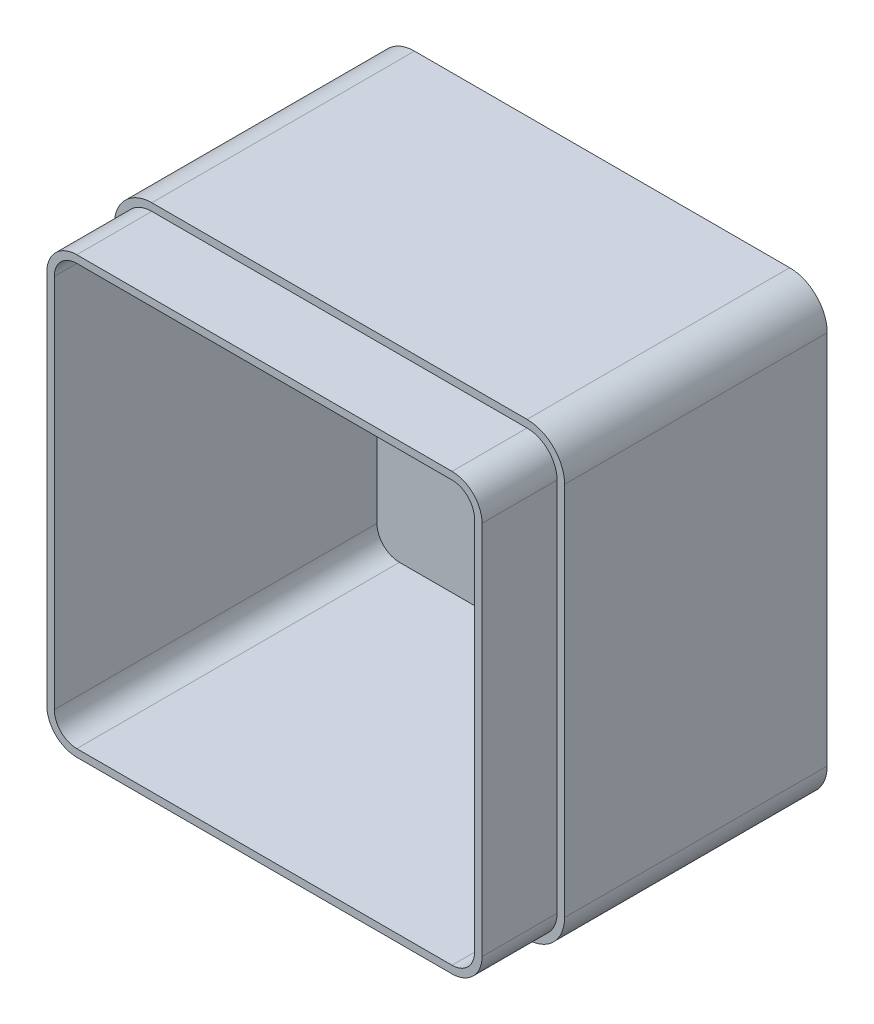
SolidWorks part; units mm, degrees
ref_plane "Front" through (0, 0, 0) normal (0, 0, 1) x (1, 0, 0)
ref_plane "Top" through (0, 0, 0) normal (0, 1, 0) x (1, 0, 0)
ref_plane "Right" through (0, 0, 0) normal (1, 0, 0) x (0, 0, -1)
sketch "Sketch1" plane through (0, 0, 0) normal (0, 0, 1) x (1, 0, 0)
  line L1 (-60, 60) -> (60, 60)
  line L2 (-60, 60) -> (-60, -60)
  line L3 (-60, -60) -> (60, -60)
  line L4 (60, 60) -> (60, -60)
  line L5 (-60, 60) -> (60, -60) construction
  line L6 (-60, -60) -> (60, 60) construction
  point P0 (0, 0)
  dimension "D1" = 120
  dimension "D2" = 120
extrude "Boss-Extrude1" add sketch "Sketch1" along normal blind 90
fillet "Fillet1" radius 10 4 edges at (60, -60, 45) (-60, -60, 45) (60, 60, 45) (-60, 60, 45)
shell "Shell1" thickness 4
sketch "Sketch2" plane through (0, 0, 90) normal (0, 0, 1) x (1, 0, 0)
  line L0 (-50, -58) -> (50, -58)
  line L1 (58, -50) -> (58, 50)
  line L2 (50, 58) -> (-50, 58)
  line L3 (-58, 50) -> (-58, -50)
  line L4 (-50, -60) -> (50, -60)
  line L5 (60, -50) -> (60, 50)
  line L6 (50, 60) -> (-50, 60)
  line L7 (-60, 50) -> (-60, -50)
  line L8 (-50, -60) -> (50, -60)
  line L9 (60, -50) -> (60, 50)
  line L10 (50, 60) -> (-50, 60)
  line L11 (-60, 50) -> (-60, -50)
  arc A0 (50, -58) -> (58, -50) centre (50, -50) ccw
  arc A1 (58, 50) -> (50, 58) centre (50, 50) ccw
  arc A2 (-50, 58) -> (-58, 50) centre (-50, 50) ccw
  arc A3 (-58, -50) -> (-50, -58) centre (-50, -50) ccw
  arc A4 (50, -60) -> (60, -50) centre (50, -50) ccw
  arc A5 (60, 50) -> (50, 60) centre (50, 50) ccw
  arc A6 (-50, 60) -> (-60, 50) centre (-50, 50) ccw
  arc A7 (-60, -50) -> (-50, -60) centre (-50, -50) ccw
  arc A8 (50, -60) -> (60, -50) centre (50, -50) ccw
  arc A9 (60, 50) -> (50, 60) centre (50, 50) ccw
  arc A10 (-50, 60) -> (-60, 50) centre (-50, 50) ccw
  arc A11 (-60, -50) -> (-50, -60) centre (-50, -50) ccw
  dimension "D1" = 0
  dimension "D2" = 2
extrude "Cut-Extrude1" cut sketch "Sketch2" against normal blind 20
